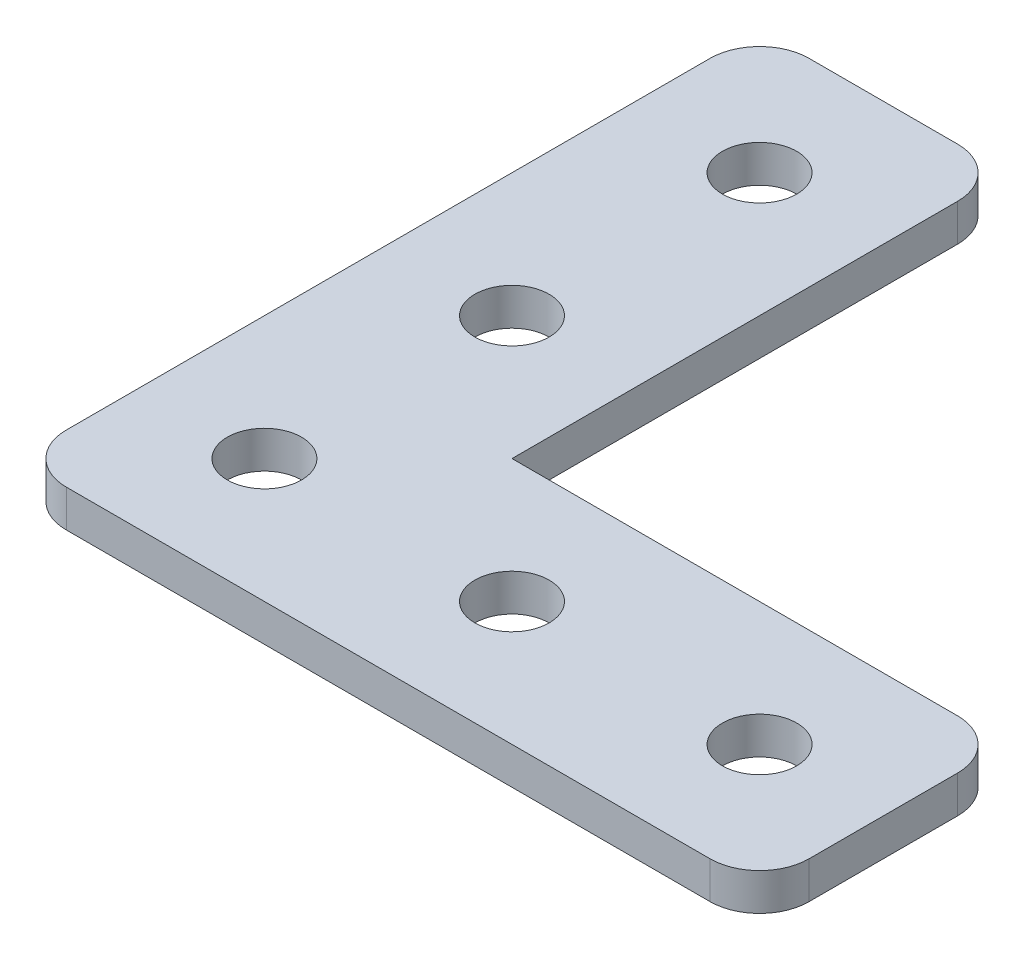
SolidWorks part; units mm, degrees
material "1060 合金"
ref_plane "正面" through (0, 0, 0) normal (0, 0, 1) x (1, 0, 0)
ref_plane "平面" through (0, 0, 0) normal (0, 1, 0) x (1, 0, 0)
ref_plane "右側面" through (0, 0, 0) normal (1, 0, 0) x (0, 0, -1)
sketch "ｽｹｯﾁ2" plane through (0, 0, 0) normal (0, 1, 0) x (1, 0, 0)
  line L0 (0, 0) -> (30, 0)
  line L1 (30, 0) -> (30, 10)
  line L2 (30, 10) -> (10, 30)
  line L3 (10, 30) -> (0, 30)
  line L4 (0, 30) -> (0, 0)
  line L5 (0, 0) -> (20, 20) construction
  line L6 (30, 5) -> (0, 5) construction
  line L7 (10, 30) -> (10, 10)
  line L8 (10, 10) -> (30, 10)
  circle A0 centre (5, 5) radius 1.5
  circle A1 centre (25, 5) radius 1.5
  circle A2 centre (5, 25) radius 1.5
  circle A5 centre (15, 5) radius 1.5
  circle A6 centre (5, 15) radius 1.5
  dimension "D1" = 10
  dimension "D2" = 3
  dimension "D3" = 5
  dimension "D4" = 5
  dimension "D5" = 20
  dimension "D6" = 10
extrude "ﾎﾞｽ - 押し出し1" add sketch "ｽｹｯﾁ2" along normal blind 1.5 contours L8 L7 L3 L4 L0 L1 A2 A1 A0 A5 A6
fillet "ﾌｨﾚｯﾄ1" radius 2 5 edges at (0, 0.75, 0) (30, 0.75, 0) (0, 0.75, -30) (30, 0.75, -10) (10, 0.75, -30)
